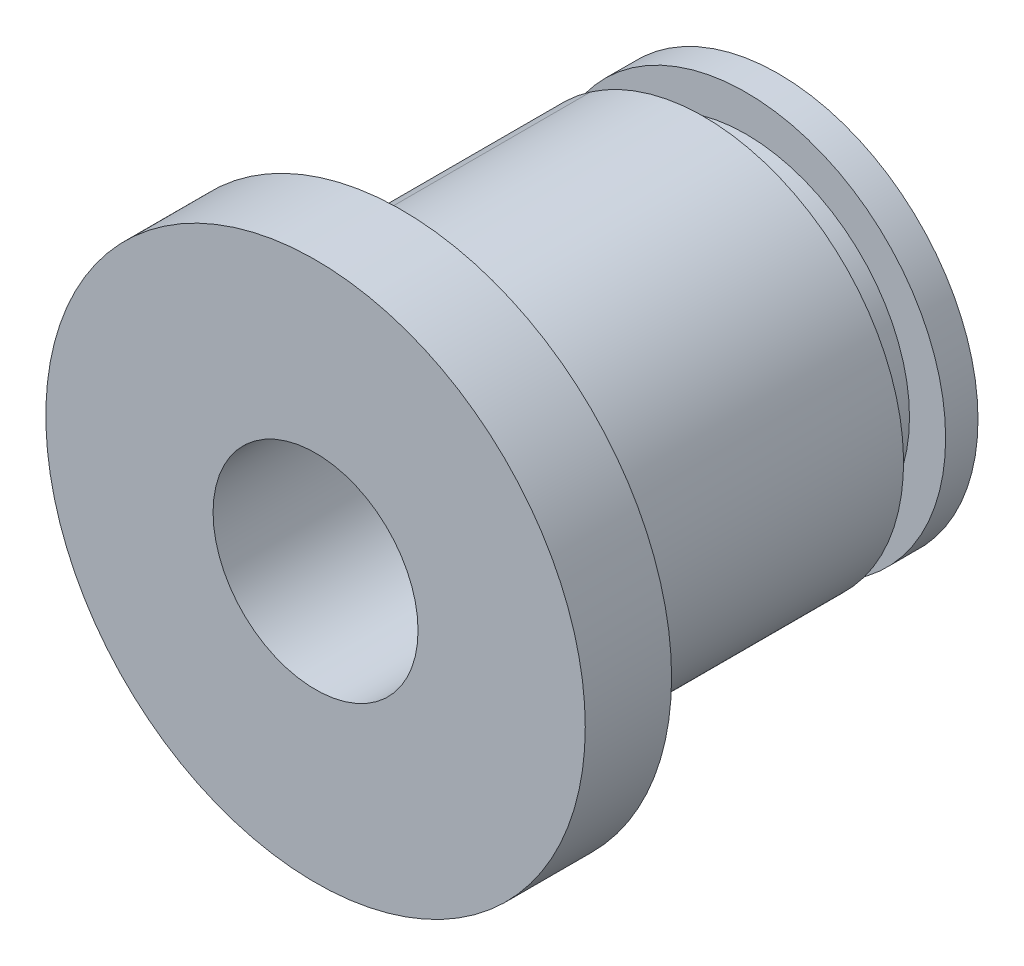
SolidWorks part; units mm, degrees
material "AISI 4130 Steel, annealed at 865C"
ref_plane "Front Plane" through (0, 0, 0) normal (0, 0, 1) x (1, 0, 0)
ref_plane "Top Plane" through (0, 0, 0) normal (0, 1, 0) x (1, 0, 0)
ref_plane "Right Plane" through (0, 0, 0) normal (1, 0, 0) x (0, 0, -1)
sketch "Sketch1" plane through (0, 0, 0) normal (0, 0, 1) x (1, 0, 0)
  circle A0 centre (0, 0) radius 6.35
  dimension "D1" = 12.7
extrude "Boss-Extrude1" add sketch "Sketch1" along normal blind 2.032
sketch "Sketch2" plane through (0, 0, 0) normal (0, 0, -1) x (-1, 0, 0)
  circle A0 centre (0, 0) radius 4.699
  dimension "D1" = 9.398
extrude "Boss-Extrude2" add sketch "Sketch2" along normal blind 8.8646
ref_axis "Axis1" through (0, 0, 6.5491) along (0, 0, -1)
sketch "Sketch4" plane through (0, 0, 0) normal (1, 0, 0) x (0, 0, -1)
  line L0 (0, -4.699) -> (0, 4.699) construction
  line L1 (0, -4.699) -> (0, 4.699)
  line L2 (7.112, 4.699) -> (7.112, -4.699)
  line L3 (8.8646, 4.699) -> (0, 4.699) construction
  line L4 (0, -4.699) -> (8.8646, -4.699) construction
  line L5 (0, 4.699) -> (8.8646, 4.699)
  line L6 (0, -4.699) -> (8.8646, -4.699)
  line L7 (8.8646, -4.699) -> (8.8646, 4.699) construction
  line L8 (8.1026, 4.699) -> (8.1026, -4.699)
  line L9 (7.112, 3.8481) -> (8.1026, 3.8481)
  line L10 (7.112, 0) -> (8.1026, 0)
  dimension "D1" = 7.112
  dimension "D2" = 0.9906
  dimension "D3" = 3.8481
revolve "Cut-Revolve1" cut sketch "Sketch4" angle 360 about axis through (0, 0, 6.5491) along (0, 0, -1)
sketch3d "3DSketch1"
  line L0 (2.6418, -3.886, 0) -> (-2.6678, 3.8683, 0)
  circle A2 centre (0, 0, 0) radius 4.699 construction
  point P4 (0, 0, -4.699)
split line "Split Line3"
sketch "Sketch8" plane through (0, 0, 2.032) normal (0, 0, 1) x (1, 0, 0)
  circle A0 centre (0, 0) radius 2.413
extrude "Cut-Extrude2" cut sketch "Sketch8" against normal blind 15.24
